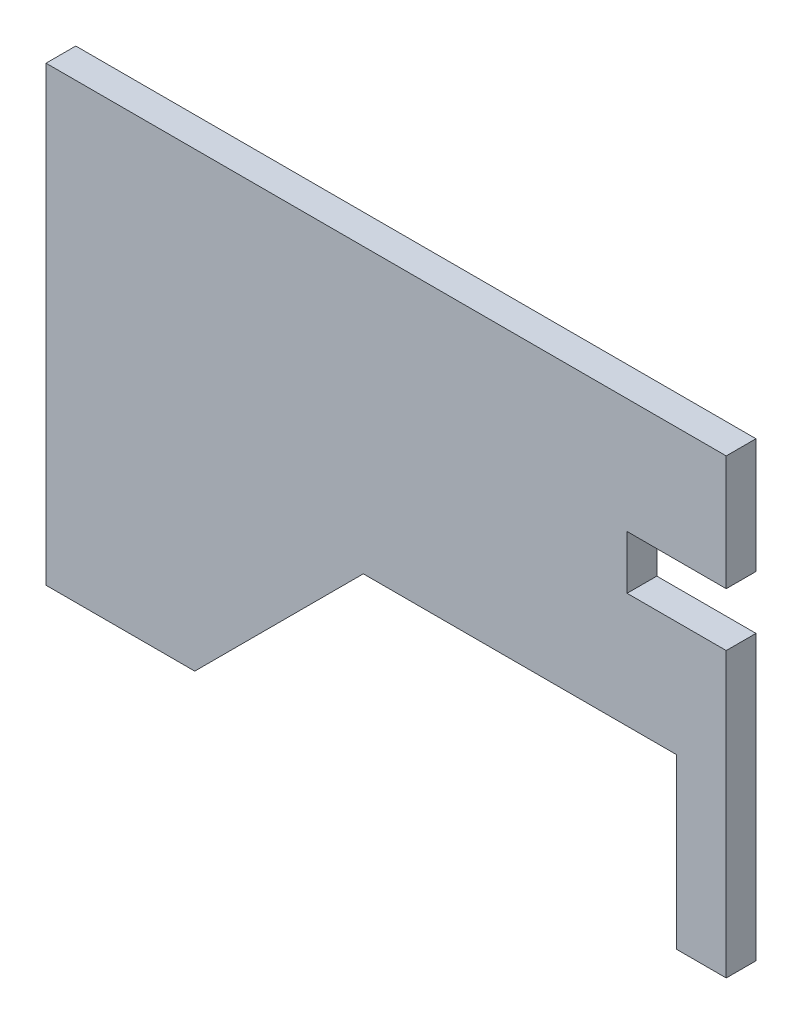
SolidWorks part; units mm, degrees
ref_plane "Front Plane" through (0, 0, 0) normal (0, 0, 1) x (1, 0, 0)
ref_plane "Top Plane" through (0, 0, 0) normal (0, 1, 0) x (1, 0, 0)
ref_plane "Right Plane" through (0, 0, 0) normal (1, 0, 0) x (0, 0, -1)
sketch "Sketch1" plane through (0, 0, 0) normal (0, 0, 1) x (1, 0, 0)
  line L51 (-26, -11) -> (36, -11)
  line L52 (36, -6) -> (36, -11)
  line L53 (36, -6) -> (26, -6)
  line L54 (26, -6) -> (26, -4.6)
  line L55 (23, -4.6) -> (26, -4.6)
  line L56 (23, -1) -> (23, -4.6)
  line L57 (23, -1) -> (26, -1)
  line L58 (26, -1) -> (26, 1)
  line L59 (23, 1) -> (26, 1)
  line L60 (23, 1) -> (23, 4.6)
  line L61 (23, 4.6) -> (26, 4.6)
  line L62 (26, 6) -> (26, 4.6)
  line L63 (36, 6) -> (26, 6)
  line L64 (36, 6) -> (36, 11)
  line L65 (-26, 11) -> (36, 11)
  line L66 (-26, 11) -> (-26, 4.6)
  line L67 (-23, 4.6) -> (-26, 4.6)
  line L68 (-23, 4.6) -> (-23, 1)
  line L69 (-23, 1) -> (-26, 1)
  line L70 (-26, -1) -> (-26, 1)
  line L71 (-23, -1) -> (-26, -1)
  line L72 (-23, -4.6) -> (-23, -1)
  line L73 (-23, -4.6) -> (-26, -4.6)
  line L74 (-26, -11) -> (-26, -4.6)
  point P0 (2.283, -5.1595)
  point P5 (24.8, -2.8)
  point P9 (36.3, -11.3)
  point P16 (-24.8, -2.8)
extrude "Boss-Extrude2" add sketch "Sketch1" along normal blind 2.4
sketch "Sketch3" plane through (0, 0, 2.4) normal (0, 0, 1) x (1, 0, 0)
  line L0 (-29.3, -14.3) -> (-29.3, -31.3)
  line L2 (-29.3, -14.3) -> (-29.3, 14.3)
  line L3 (-29.3, 14.3) -> (29.3, 14.3)
  line L4 (29.3, -2.7) -> (29.3, 2.7)
  line L5 (-29.3, -14.3) -> (29.3, 14.3) construction
  line L6 (34.3, -14.3) -> (2.7, -14.3)
  line L11 (2.7, -14.3) -> (-14.3, -31.3)
  line L12 (39.3, -14.3) -> (39.3, -31.3)
  line L13 (39.3, 2.7) -> (29.3, 2.7)
  line L14 (39.3, 2.7) -> (39.3, 14.3)
  line L15 (39.3, 14.3) -> (29.3, 14.3)
  line L17 (39.3, 2.7) -> (29.3, 14.3) construction
  line L18 (39.3, 14.3) -> (29.3, 2.7) construction
  line L19 (39.3, -2.7) -> (29.3, -2.7)
  line L20 (39.3, -2.7) -> (39.3, -14.3)
  line L23 (-14.3, -31.3) -> (-29.3, -31.3)
  line L24 (39.3, -14.3) -> (29.3, -2.7) construction
  line L25 (39.3, -31.3) -> (34.3, -31.3)
  line L26 (34.3, -31.3) -> (34.3, -14.3)
  point P0 (0, 0)
  point P6 (34.3, -8.5)
  point P12 (34.3, 8.5)
  point P21 (0, 0)
  dimension "D1" = 58.6
  dimension "D2" = 28.6
  dimension "D3" = 17
  dimension "D4" = 17
  dimension "D5" = 5
  dimension "D6" = 17
  dimension "D7" = 5.4
  dimension "D8" = 10
  dimension "D9" = 31.6
  dimension "D10" = 10
  dimension "D11" = 11.6
  dimension "D12" = 11.6
  dimension "D13" = 15
  dimension "D14" = 135
extrude "Boss-Extrude3" add sketch "Sketch3" along normal blind 3 contours L4 L13 L14 L15 L3 L2 L0 L23 L11 L6 L26 L25 L12 L20 L19
sketch "Sketch4" plane through (0, 0, 0) normal (0, 0, -1) x (-1, 0, 0)
  line L0 (-26, 1) -> (26, 1)
  line L1 (26, 1) -> (26, -1)
  line L2 (26, -1) -> (-26, -1)
  line L3 (-26, -1) -> (-26, 1)
extrude "Cut-Extrude1" cut sketch "Sketch4" against normal up to surface (2.4 mm away) up to face at (6, 0, 2.4)
